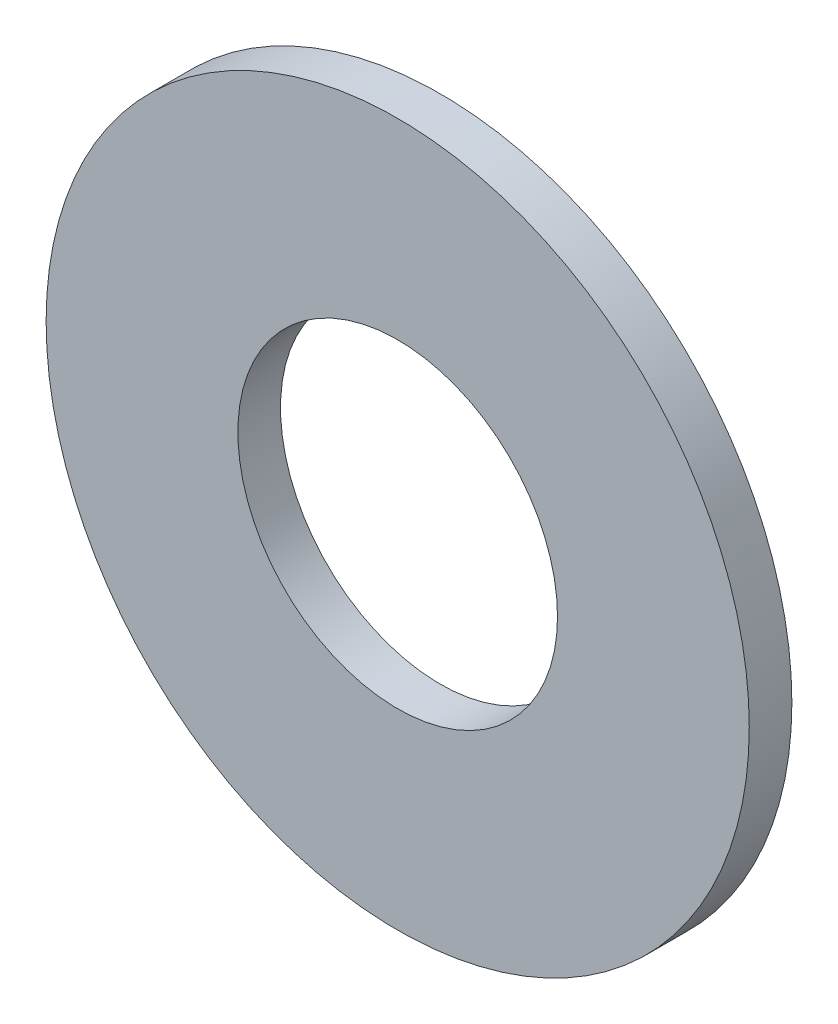
SolidWorks part; units mm, degrees
ref_plane "Front Plane" through (0, 0, 0) normal (0, 0, 1) x (1, 0, 0)
ref_plane "Top Plane" through (0, 0, 0) normal (0, 1, 0) x (1, 0, 0)
ref_plane "Right Plane" through (0, 0, 0) normal (1, 0, 0) x (0, 0, -1)
sketch "Sketch1" plane through (0, 0, 0) normal (0, 0, 1) x (1, 0, 0)
  circle A0 centre (0, 0) radius 82.5
  circle A1 centre (0, 0) radius 37.5
  dimension "D1" = 75
  dimension "D2" = 165
extrude "Boss-Extrude1" add sketch "Sketch1" along normal blind 10
